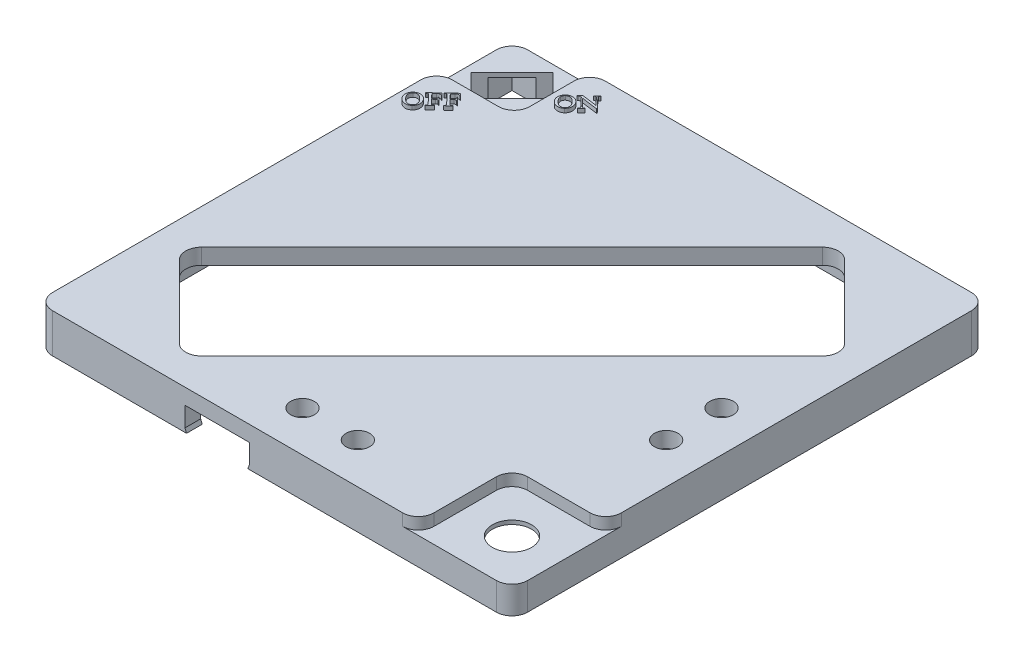
SolidWorks part; units mm, degrees
ref_plane "Front Plane" through (0, 0, 0) normal (0, 0, 1) x (1, 0, 0)
ref_plane "Top Plane" through (0, 0, 0) normal (0, 1, 0) x (1, 0, 0)
ref_plane "Right Plane" through (0, 0, 0) normal (1, 0, 0) x (0, 0, -1)
sketch "Sketch3" plane through (0, 0, 0) normal (0, 1, 0) x (1, 0, 0)
  line L1 (-30.3, -30.3) -> (30.3, -30.3)
  line L2 (-30.3, -30.3) -> (-30.3, 30.3)
  line L3 (-30.3, 30.3) -> (30.3, 30.3)
  line L4 (30.3, -30.3) -> (30.3, 30.3)
  line L5 (-30.3, -30.3) -> (30.3, 30.3) construction
  line L6 (-30.3, 30.3) -> (30.3, -30.3) construction
  point P0 (0, 0)
  dimension "D2" = 60.6
  dimension "D1" = 60.6
extrude "Boss-Extrude1" add sketch "Sketch3" along normal blind 5
sketch "Sketch4" plane through (0, 5, 0) normal (0, 1, 0) x (1, 0, 0)
  line L0 (-15.2028, -27.2236) -> (27.2236, 15.2028)
  line L1 (-15.2028, -27.2236) -> (-27.2236, -15.2028)
  line L2 (27.2236, 15.2028) -> (15.2028, 27.2236)
  line L3 (-27.2236, -15.2028) -> (15.2028, 27.2236)
  line L4 (-15.2028, -27.2236) -> (15.2028, 27.2236) construction
  line L5 (27.2236, 15.2028) -> (-27.2236, -15.2028) construction
  line L6 (30.3, 30.3) -> (-30.3, -30.3) construction
  point P1 (0, 0)
  dimension "D1" = 60
  dimension "D2" = 17
extrude "Cut-Extrude1" cut sketch "Sketch4" against normal through all
sketch "Sketch7" plane through (0, 0, 0) normal (0, -1, 0) x (1, 0, 0)
  line L0 (-30.3, -30.3) -> (-30.3, 30.3) construction
  line L1 (28.3, 28.3) -> (-28.3, 28.3)
  line L2 (28.3, 28.3) -> (28.3, -28.3)
  line L3 (28.3, -28.3) -> (-28.3, -28.3)
  line L4 (-28.3, 28.3) -> (-28.3, -28.3)
  line L5 (28.3, 28.3) -> (-28.3, -28.3) construction
  line L6 (28.3, -28.3) -> (-28.3, 28.3) construction
  line L7 (30.3, -30.3) -> (-30.3, -30.3) construction
  point P0 (0, 0)
  dimension "D1" = 2
  dimension "D2" = 2
extrude "Cut-Extrude11" cut sketch "Sketch7" against normal blind 3
sketch "Sketch9" plane through (0, 3, 0) normal (0, -1, 0) x (1, 0, 0)
  line L0 (30.3, 30.3) -> (-30.3, -30.3) construction
  line L1 (-30.3, 30.3) -> (30.3, 30.3) construction
  line L2 (30.3, 30.3) -> (30.3, -30.3) construction
  line L3 (30.3, 1.93) -> (22.6397, 1.93) construction
  circle A0 centre (25.12, -1.6) radius 1.5
  circle A1 centre (25.12, 5.46) radius 1.5
  circle A2 centre (5.46, 25.12) radius 1.5
  circle A3 centre (-1.6, 25.12) radius 1.5
  dimension "D1" = 3
  dimension "D2" = 31.9
  dimension "D3" = 5.18
  dimension "D4" = 3.53
extrude "Cut-Extrude12" cut sketch "Sketch9" against normal through all
sketch "Sketch11" plane through (0, 3, 0) normal (0, -1, 0) x (1, 0, 0)
  line L0 (-30.3, -30.3) -> (30.3, 30.3) construction
  line L1 (24.3957, 29.1333) -> (29.1333, 24.3957)
  line L2 (24.3957, 29.1333) -> (19.658, 24.3957)
  line L3 (29.1333, 24.3957) -> (24.3957, 19.658)
  line L4 (19.658, 24.3957) -> (24.3957, 19.658)
  line L5 (24.3957, 29.1333) -> (24.3957, 19.658) construction
  line L6 (29.1333, 24.3957) -> (19.658, 24.3957) construction
  line L7 (-26.5523, -21.3197) -> (-21.3197, -26.5523)
  line L8 (-26.5523, -21.3197) -> (-29.3808, -24.1482)
  line L9 (-21.3197, -26.5523) -> (-24.1482, -29.3808)
  line L10 (-29.3808, -24.1482) -> (-24.1482, -29.3808)
  line L11 (-26.5523, -21.3197) -> (-24.1482, -29.3808) construction
  line L12 (-21.3197, -26.5523) -> (-29.3808, -24.1482) construction
  point P4 (0, 0)
  point P5 (24.3957, 24.3957)
  point P6 (-25.3503, -25.3503)
  dimension "D1" = 6.7
  dimension "D2" = 6.7
  dimension "D3" = 5
  dimension "D4" = 7.4
  dimension "D5" = 4
  dimension "D6" = 5
sketch "Sketch12" plane through (0, 0, 0) normal (0, -1, 0) x (1, 0, 0)
  line L0 (30.3, -30.3) -> (-30.3, -30.3) construction
  line L1 (-30.3, -30.3) -> (-30.3, 30.3) construction
  circle A0 centre (-21.6, -9.72) radius 2.75
  dimension "D1" = 5.5
  dimension "D2" = 20.58
  dimension "D3" = 8.7
extrude "Cut-Extrude14" cut sketch "Sketch12" against normal blind 4.5
sketch "Sketch16" plane through (0, 3, 0) normal (0, -1, 0) x (-1, 0, 0)
  line L0 (-25.7025, 2.9823) -> (-25.7025, 0.2177)
  line L1 (-25.12, -5.46) -> (-25.12, 1.6) construction
  line L2 (-25.12, -1.93) -> (-21.6271, -1.93) construction
  line L3 (-25.7025, -6.8423) -> (-25.7025, -4.0777)
  line L4 (-30.3, -30.3) -> (30.3, 30.3) construction
  line L6 (2.9823, -25.7025) -> (0.2177, -25.7025)
  arc A0 (-25.7025, 0.2177) -> (-25.7025, 2.9823) centre (-25.12, 1.6) ccw
  circle A1 centre (-25.12, 1.6) radius 1.5 construction
  arc A2 (-25.7025, -4.0777) -> (-25.7025, -6.8423) centre (-25.12, -5.46) cw
  arc A4 (0.2177, -25.7025) -> (2.9823, -25.7025) centre (1.6, -25.12) cw
sketch "Sketch17" plane through (0, 3, 0) normal (0, -1, 0) x (1, 0, 0)
  line L0 (18.3515, 18.3515) -> (30.3, 18.3515)
  line L1 (18.3515, 18.3515) -> (18.3515, 30.3)
  line L2 (30.3, 18.3515) -> (30.3, 30.3)
  line L3 (18.3515, 30.3) -> (30.3, 30.3)
  line L4 (18.3515, 18.3515) -> (30.3, 30.3) construction
  line L5 (30.3, 18.3515) -> (18.3515, 30.3) construction
  line L6 (-20.4005, -20.6734) -> (-30.3, -20.6734)
  line L7 (-20.4005, -20.6734) -> (-20.4005, -30.3)
  line L8 (-30.3, -20.6734) -> (-30.3, -30.3)
  line L9 (-20.4005, -30.3) -> (-30.3, -30.3)
  line L10 (-20.4005, -20.6734) -> (-30.3, -30.3) construction
  line L11 (-30.3, -20.6734) -> (-20.4005, -30.3) construction
  line L12 (-30.3, 30.3) -> (30.3, 30.3) construction
  line L13 (30.3, 30.3) -> (30.3, -30.3) construction
  line L14 (30.3, -30.3) -> (-30.3, -30.3) construction
  line L15 (-30.3, -30.3) -> (-30.3, 30.3) construction
  line L16 (-30.3, -30.3) -> (30.3, 30.3) construction
  point P1 (24.3257, 24.3257)
  point P2 (-25.3503, -25.4867)
extrude "Cut-Extrude15" cut sketch "Sketch17" against normal through all
sketch "Sketch20" plane through (0, 0, 30.3) normal (0, 0, 1) x (1, 0, 0)
  line L0 (-7.3, 0) -> (-7.3, 5) construction
  line L1 (-30.3, 0) -> (30.3, 0) construction
  line L2 (-15.2028, 5) -> (15.2028, 5) construction
  line L3 (-11.2, 0) -> (-3.4, 0)
  line L4 (-3.4, 0) -> (-3.2, 0.5)
  line L5 (-3.2, 0.5) -> (-3.2, 3)
  line L6 (-3.2, 3) -> (-11.4, 3)
  line L7 (-11.2, 0) -> (-11.4, 0.5)
  line L8 (-11.4, 0.5) -> (-11.4, 3)
  line L9 (30.3, 3) -> (30.3, 0) construction
  point P6 (-7.3, 3)
  point P14 (-7.3, 3)
  dimension "D1" = 4.1
  dimension "D2" = 3.9
  dimension "D3" = 2.5
  dimension "D4" = 3
  dimension "D5" = 33.5
extrude "Cut-Extrude16" cut sketch "Sketch20" against normal up to next
sketch "Sketch21" plane through (0, 3, 0) normal (0, -1, 0) x (1, 0, 0)
  line L0 (-30.3, -30.3) -> (30.3, 30.3) construction
  line L1 (30.3, 30.3) -> (18.3515, 30.3)
  line L2 (30.3, 30.3) -> (30.3, 18.3515)
  line L3 (30.3, 18.3515) -> (18.3515, 18.3515)
  line L4 (18.3515, 30.3) -> (18.3515, 18.3515)
  line L5 (-30.3, -30.3) -> (-20.3988, -30.3)
  line L6 (-30.3, -30.3) -> (-30.3, -20.3988)
  line L7 (-30.3, -20.3988) -> (-20.3988, -20.3988)
  line L8 (-20.3988, -30.3) -> (-20.3988, -20.3988)
extrude "Boss-Extrude2" add sketch "Sketch21" against normal blind 0.5
sketch "Sketch22" plane through (0, 3.5, 0) normal (0, 1, 0) x (1, 0, 0)
  line L0 (29.1333, -24.3957) -> (19.658, -24.3957) construction
  line L1 (-29.3873, 24.1547) -> (-24.1547, 29.3873)
  line L2 (-29.3873, 24.1547) -> (-26.5458, 21.3132)
  line L3 (-24.1547, 29.3873) -> (-21.3132, 26.5458)
  line L4 (-26.5458, 21.3132) -> (-21.3132, 26.5458)
  line L5 (-29.3873, 24.1547) -> (-21.3132, 26.5458) construction
  line L6 (-24.1547, 29.3873) -> (-26.5458, 21.3132) construction
  circle A0 centre (24.3957, -24.3957) radius 2.5012
  point P5 (-25.3503, 25.3503)
extrude "Cut-Extrude17" cut sketch "Sketch22" against normal through all
fillet "Fillet3" radius 2 14 edges at (-15.2028, 4, 27.2236) (-27.2236, 4, 15.2028) (15.2028, 4, -27.2236) (27.2236, 4, -15.2028) (30.3, 4.25, 18.3515) (18.3515, 4.25, 18.3515) (18.3515, 4.25, 30.3) (-30.3, 4.25, -20.6734) (-20.4005, 4.25, -30.3) (-20.4005, 4.25, -20.6734) (-30.3, 2.5, 30.3) (30.3, 1.75, 30.3) (30.3, 2.5, -30.3) (-30.3, 1.75, -30.3)
sketch "Sketch23" plane through (0, 5, 0) normal (0, 1, 0) x (1, 0, 0)
  line L0 (-28.3401, 14.0998) -> (-13.6313, 27.8716) construction
  text T0 "OFF           ON" font "Times New Roman" height 2
extrude "Boss-Extrude3" add sketch "Sketch23" along normal blind 0.5
equation "\"pcb_w\"= 60.6"
equation "\"pcb_H\"= 60.6"
equation "\"D1@Sketch3\"=\"pcb_H\""
equation "\"D2@Sketch3\"= \"pcb_w\""
equation "\"case_H\"= 5"
equation "\"D1@Boss-Extrude1\"=\"case_H\""
equation "\"AA_L\"= 60"
equation "\"D1@Sketch4\"=\"AA_L\""
equation "\"AA_d\"= 17"
equation "\"D2@Sketch4\"=\"AA_d\""
equation "\"comp_h\"= 3"
equation "\"D1\"= \"comp_h\""
equation "\"D5@Sketch14\"=41-3.9"
